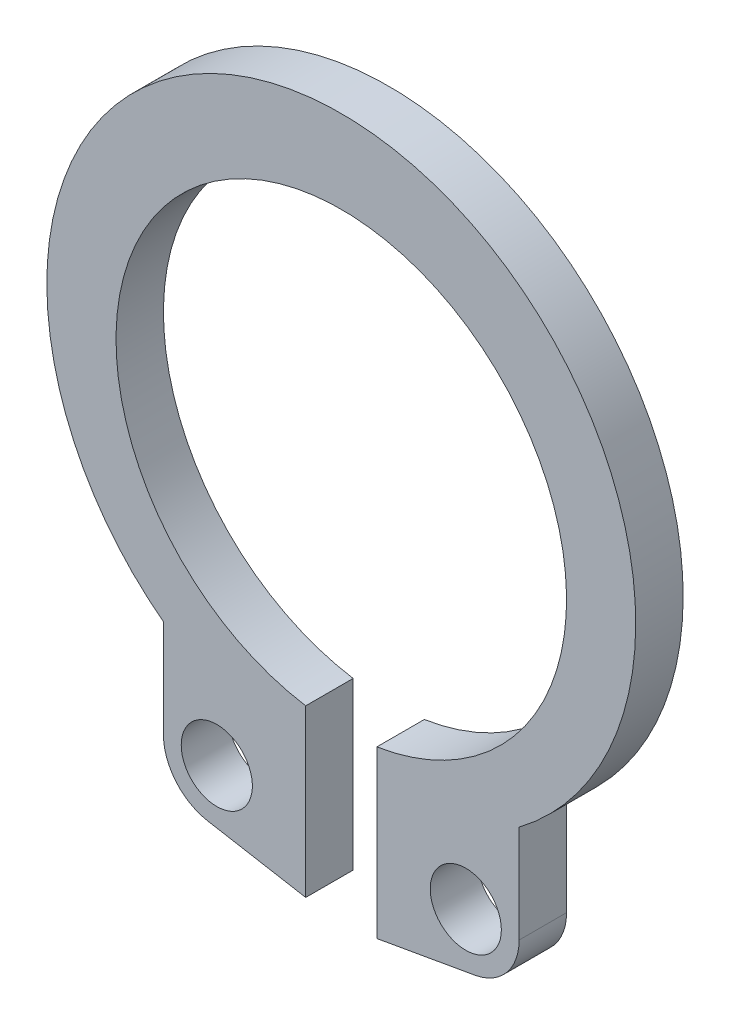
SolidWorks part; units mm, degrees
ref_plane "Plane1" through (0, 0, 0) normal (0, 0, 1) x (1, 0, 0)
ref_plane "Plane2" through (0, 0, 0) normal (0, 1, 0) x (1, 0, 0)
ref_plane "Plane3" through (0, 0, 0) normal (1, 0, 0) x (0, 0, -1)
extrude "Base-Extrude" add sketch "Sketch1" along normal blind 0.8
sketch "Sketch1" plane through (0, 0, 0) normal (0, 0, 1) x (1, 0, 0)
  line L0 (-0.6, -3.7523) -> (-0.6, -6.5523)
  line L1 (0, 0.2333) -> (0, -2) construction
  line L2 (0.6, -3.7523) -> (0.6, -6.5523)
  line L3 (0, 5.2) -> (0, 3.8) construction
  line L4 (-3, -3.7249) -> (-3, -6.1291)
  line L5 (-3, -6.1291) -> (-0.6, -6.5523)
  line L6 (3, -3.7249) -> (3, -6.1291)
  line L7 (0.6, -6.5523) -> (3, -6.1291)
  arc A1 (0.6, -3.7523) -> (-0.6, -3.7523) centre (0, 0) ccw
  circle A2 centre (0, -2) radius 0.6 construction
  arc A6 (3, -3.7249) -> (-3, -3.7249) centre (0, 0.2333) ccw
  point P3 (0, 3.8)
  point P4 (0, 5.2)
  dimension "D1" = 80
  dimension "D4" = 9.9333
  dimension "D5" = 1.2
  dimension "_d2" = 7.6
  dimension "D9" = 2.4
  dimension "_d5" = 1.2
  dimension "a" = 2.8
  dimension "b" = 1.4
fillet "Fillet1" radius 0.9 2 edges at (3, -6.1291, 0.4) (-3, -6.1291, 0.4)
sketch "Sketch2" plane through (0, 0, 0.8) normal (0, 0, 1) x (1, 0, 0)
  circle A0 centre (2.1, -5.374) radius 0.6
  arc A2 (2.2563, -6.2603) -> (3, -5.374) centre (2.1, -5.374) ccw construction
  arc A3 (2.2563, -6.2603) -> (3, -5.374) centre (2.1, -5.374) ccw construction
  dimension "D1" = 1.2
extrude "Cut-Extrude1" cut sketch "Sketch2" against normal through all
mirror "Mirror1" about plane through (0, 0, 0) normal (1, 0, 0) of "Cut-Extrude1"
equation "\"D5@Sketch1\" = \"_d5@Sketch1\""
equation "\"D9@Sketch1\" = \"_d5@Sketch1\" * 2"
equation "\"D4@Sketch1\" = \"_d2@Sketch1\" + \"b@Sketch1\" + \"a@Sketch1\" / 3"
equation "\"D1@Fillet1\" =0.75 * \"_d5@Sketch1\""
equation "\"D1@Sketch2\" = \"_d5@Sketch1\""
